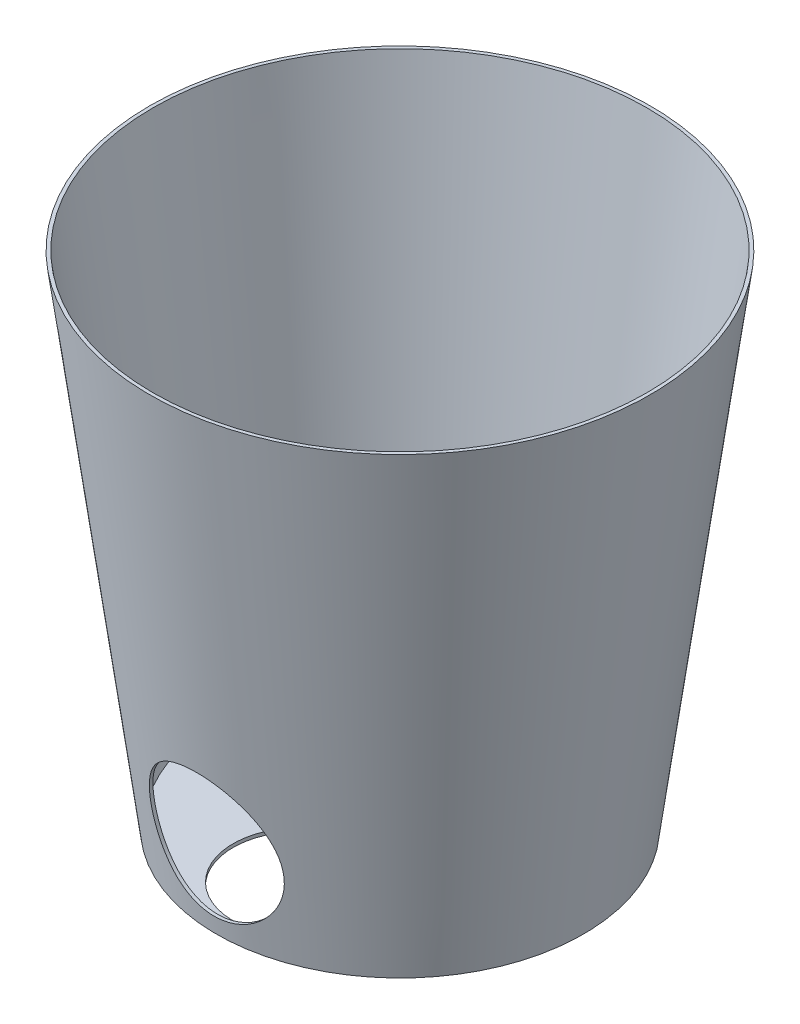
SolidWorks part; units mm, degrees
ref_plane "前基準面" through (0, 0, 0) normal (0, 0, 1) x (1, 0, 0)
ref_plane "上基準面" through (0, 0, 0) normal (0, 1, 0) x (1, 0, 0)
ref_plane "右基準面" through (0, 0, 0) normal (1, 0, 0) x (0, 0, -1)
sketch "草圖1" plane through (0, 0, 0) normal (0, 0, 1) x (1, 0, 0)
  line L0 (-150, 300) -> (-110, 0)
  line L1 (-110, 0) -> (0, 0)
  line L3 (-150, 300) -> (0, 300)
  line L4 (0, 300) -> (0, 0)
  point P5 (28.5062, 78.2097)
  point P7 (0, 6.07)
  point P8 (0, 0)
  point P10 (104.2755, 70.3454)
  dimension "D1" = 150
  dimension "D2" = 110
  dimension "D3" = 300
revolve "旋轉1" add sketch "草圖1" angle 360 about L4
shell "薄殼1" thickness 2
sketch "草圖2" plane through (0, 0, 0) normal (0, 0, 1) x (1, 0, 0)
  circle A0 centre (0, 50) radius 40
  point P2 (0, 69.8624)
  point P3 (0, 0)
  dimension "D1" = 80
  dimension "D2" = 50
extrude "除料-伸長1" cut sketch "草圖2" along normal through all contours A0
sketch "草圖3" plane through (0, 0, 0) normal (0, 1, 0) x (1, 0, 0)
  circle A0 centre (0, -60) radius 40
  dimension "D1" = 60
  dimension "D2" = 80
extrude "除料-伸長7" cut sketch "草圖3" along normal blind 10
